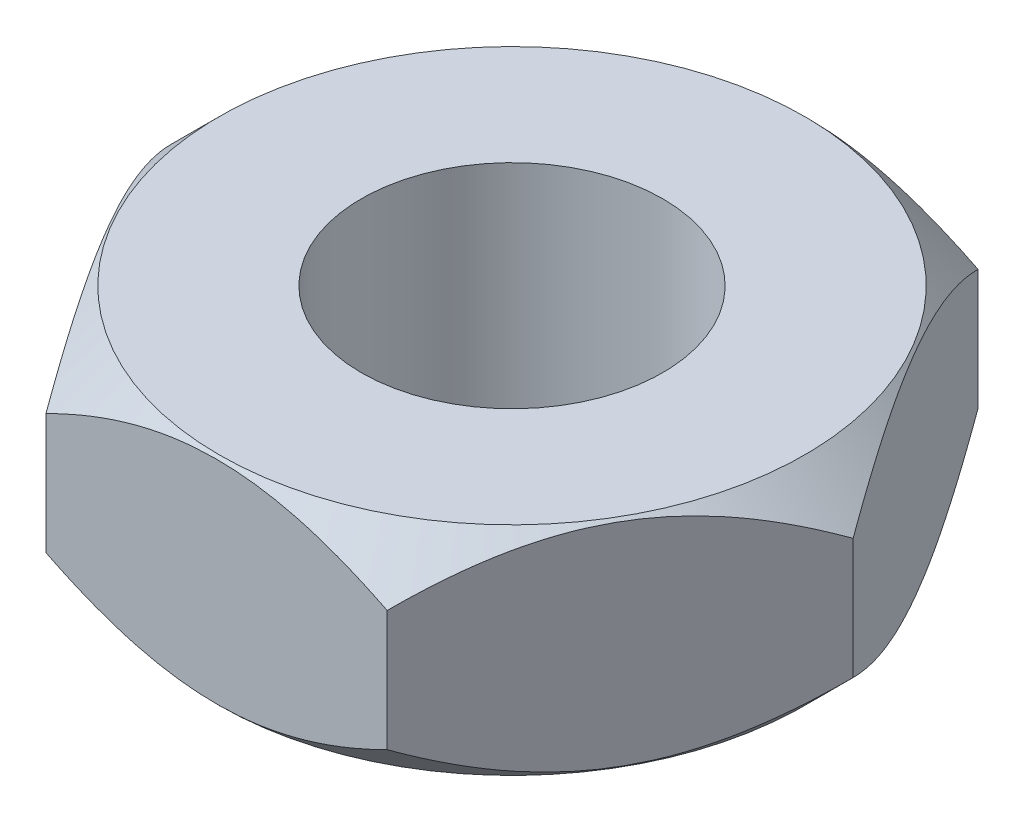
SolidWorks part; units mm, degrees
material "AISI 304"
ref_plane "Front Plane" through (0, 0, 0) normal (0, 0, 1) x (1, 0, 0)
ref_plane "Top Plane" through (0, 0, 0) normal (0, 1, 0) x (1, 0, 0)
ref_plane "Right Plane" through (0, 0, 0) normal (1, 0, 0) x (0, 0, -1)
sketch "Sketch1" plane through (0, 0, 0) normal (0, 1, 0) x (1, 0, 0)
  line L1 (1.4145, 2.45) -> (-1.4145, 2.45)
  line L2 (-1.4145, 2.45) -> (-2.829, 0)
  line L3 (-2.829, 0) -> (-1.4145, -2.45)
  line L4 (-1.4145, -2.45) -> (1.4145, -2.45)
  line L5 (1.4145, -2.45) -> (2.829, 0)
  line L6 (2.829, 0) -> (1.4145, 2.45)
  circle A0 centre (0, 0) radius 2.45 construction
  circle A1 centre (0, 0) radius 1.25
  dimension "D2" = 2.5
  dimension "D1" = 4.9
extrude "Boss-Extrude1" add sketch "Sketch1" along normal blind 1.8
ref_axis "Axis1" through (0, 1.89, 0) along (0, -1, 0)
ref_plane "Plane1" through (0, 0, 0) normal (0, 0, -1) x (-1, 0, 0)
sketch "Sketch3" plane through (0, 0, 0) normal (0, 0, -1) x (-1, 0, 0)
  line L0 (-2.829, 1.8) -> (-2.829, 1.4)
  line L1 (-2.829, 1.8) -> (-2.829, 0) construction
  line L2 (-2.829, 1.4) -> (-2.429, 1.8)
  line L3 (-2.829, 1.8) -> (-1.4145, 1.8) construction
  line L4 (-2.429, 1.8) -> (-2.829, 1.8)
  dimension "D1" = 0.4
revolve "Cut-Revolve2" cut sketch "Sketch3" angle 360 about axis through (0, 1.89, 0) along (0, -1, 0)
ref_plane "Plane2" through (0, 0.9, 0) normal (0, 1, 0) x (1, 0, 0)
mirror "Mirror1" about plane through (0, 0.9, 0) normal (0, 1, 0) of "Cut-Revolve2"
